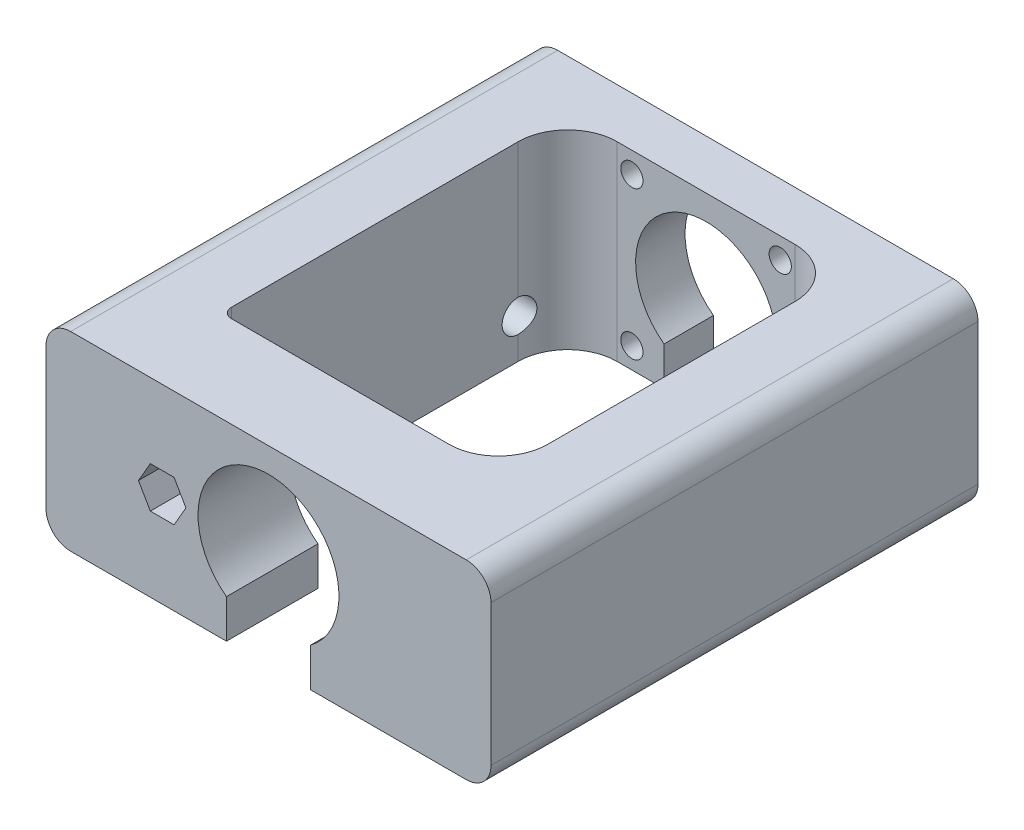
SolidWorks part; units mm, degrees
ref_plane "Front Plane" through (0, 0, 0) normal (0, 0, 1) x (1, 0, 0)
ref_plane "Top Plane" through (0, 0, 0) normal (0, 1, 0) x (1, 0, 0)
ref_plane "Right Plane" through (0, 0, 0) normal (1, 0, 0) x (0, 0, -1)
sketch "Sketch1" plane through (0, 0, 0) normal (0, 0, 1) x (1, 0, 0)
  line L0 (-15, 19.25) -> (-30, 19.25)
  line L2 (-45, 14.25) -> (-45, -14.25)
  line L4 (-15, 19.25) -> (15, 19.25)
  line L6 (15, -19.25) -> (8.5, -19.25)
  line L11 (-30, -19.25) -> (-15, -19.25)
  line L12 (-30, 19.25) -> (-40, 19.25)
  line L13 (-30, -19.25) -> (-40, -19.25)
  line L14 (-8.5, -19.25) -> (-15, -19.25)
  line L15 (0, 0) -> (0, 9.3162)
  line L16 (30, -19.25) -> (15, -19.25)
  line L17 (8.5, -16.75) -> (8.5, -11.4373)
  line L18 (-8.5, -16.75) -> (-8.5, -11.4373)
  line L19 (-8.5, -16.75) -> (-8.5, -19.25)
  line L20 (8.5, -16.75) -> (8.5, -19.25)
  line L21 (15, 19.25) -> (30, 19.25)
  line L22 (30, -19.25) -> (40, -19.25)
  line L23 (30, 19.25) -> (40, 19.25)
  line L24 (45, 14.25) -> (45, -14.25)
  arc A0 (8.5, -11.4373) -> (-8.5, -11.4373) centre (0, 0) ccw
  circle A1 centre (15, 15) radius 2.25
  circle A2 centre (-15, 15) radius 2.25
  circle A3 centre (-15, -15) radius 2.25
  circle A4 centre (15, -15) radius 2.25
  arc A19 (-40, -19.25) -> (-45, -14.25) centre (-40, -14.25) cw
  arc A20 (-40, 19.25) -> (-45, 14.25) centre (-40, 14.25) ccw
  arc A21 (40, 19.25) -> (45, 14.25) centre (40, 14.25) cw
  arc A22 (40, -19.25) -> (45, -14.25) centre (40, -14.25) ccw
  point P5 (19.25, 15)
  point P7 (-10.75, 15)
  point P13 (-10.75, -15)
  point P18 (-25.25, 0)
  point P19 (19.25, -15)
  point P20 (-15, 15)
  point P22 (15, 15)
  point P24 (15, -15)
  point P26 (-15, -15)
  point P38 (-39.75, 0)
  point P39 (-20.75, 0)
  point P51 (39.75, 0)
  dimension "D1" = 2
  dimension "D3" = 5
  dimension "D2" = 2
extrude "Boss-Extrude1" add sketch "Sketch1" along normal blind 10
sketch "Sketch2" plane through (0, 0, 10) normal (0, 0, 1) x (1, 0, 0)
  line L12 (-45, 14.25) -> (-45, -14.25)
  line L14 (-40, 19.25) -> (-28, 19.25)
  line L15 (-28, 0) -> (-28, 19.25)
  line L16 (-28, 0) -> (-28, -19.25)
  line L17 (-40, -19.25) -> (-28, -19.25)
  line L19 (40, -19.25) -> (28, -19.25)
  line L20 (28, 0) -> (28, -19.25)
  line L21 (28, 0) -> (28, 19.25)
  line L22 (40, 19.25) -> (28, 19.25)
  line L23 (45, 14.25) -> (45, -14.25)
  arc A0 (40, 19.25) -> (45, 14.25) centre (40, 14.25) cw
  arc A16 (-45, -14.25) -> (-40, -19.25) centre (-40, -14.25) ccw
  arc A17 (-40, 19.25) -> (-45, 14.25) centre (-40, 14.25) ccw
  arc A18 (45, -14.25) -> (40, -19.25) centre (40, -14.25) cw
extrude "Boss-Extrude3" add sketch "Sketch2" along normal blind 70 separate body
sketch "Sketch4" plane through (0, 0, 80) normal (0, 0, 1) x (1, 0, 0)
  line L5 (-28, -19.25) -> (-28, 19.25)
  line L7 (-45, 14.25) -> (-45, -14.25)
  line L11 (-45, 14.25) -> (-45, -14.25)
  line L21 (-40, 19.25) -> (40, 19.25)
  line L22 (-40, -19.25) -> (-8.5, -19.25)
  line L23 (-40, -19.25) -> (-28, -19.25)
  line L25 (-28, 19.25) -> (-40, 19.25)
  line L27 (-8.5, -11.4373) -> (-8.5, -19.25) construction
  line L28 (8.5, -19.25) -> (8.5, -11.4373) construction
  line L29 (40, 19.25) -> (28, 19.25)
  line L30 (28, 19.25) -> (28, -19.25)
  line L31 (28, -19.25) -> (40, -19.25)
  line L32 (45, -14.25) -> (45, 14.25)
  line L36 (45, -14.25) -> (45, 14.25)
  line L37 (-8.5, -11.4373) -> (-8.5, -19.25)
  line L38 (8.5, -19.25) -> (8.5, -11.4373)
  line L39 (8.5, -19.25) -> (40, -19.25)
  circle A1 centre (-21.5, 0) radius 3.5
  arc A2 (-45, -14.25) -> (-40, -19.25) centre (-40, -14.25) ccw
  arc A3 (-40, 19.25) -> (-45, 14.25) centre (-40, 14.25) ccw
  arc A4 (-45, -14.25) -> (-40, -19.25) centre (-40, -14.25) ccw
  arc A5 (-40, 19.25) -> (-45, 14.25) centre (-40, 14.25) ccw
  arc A11 (8.5, -11.4373) -> (-8.5, -11.4373) centre (0, 0) ccw construction
  arc A12 (45, 14.25) -> (40, 19.25) centre (40, 14.25) ccw
  arc A13 (40, -19.25) -> (45, -14.25) centre (40, -14.25) ccw
  arc A14 (45, 14.25) -> (40, 19.25) centre (40, 14.25) ccw
  arc A15 (40, -19.25) -> (45, -14.25) centre (40, -14.25) ccw
  arc A17 (8.5, -11.4373) -> (-8.5, -11.4373) centre (0, 0) ccw
  dimension "D3" = 0
  dimension "D1" = 0
extrude "Boss-Extrude4" add sketch "Sketch4" along normal blind 10
sketch "Sketch6" plane through (0, 0, 90) normal (0, 0, 1) x (1, 0, 0)
  line L6 (-40, -19.25) -> (-8.5, -19.25)
  line L8 (-40, -19.25) -> (-8.5, -19.25)
  line L9 (45, -14.25) -> (45, 14.25)
  line L10 (-45, 14.25) -> (-45, -14.25)
  line L11 (45, -14.25) -> (45, 14.25)
  line L16 (-45, 14.25) -> (-45, -14.25)
  line L21 (-16.7, 0) -> (-19.1, 4.1569)
  line L22 (-19.1, 4.1569) -> (-23.9, 4.1569)
  line L23 (-23.9, 4.1569) -> (-26.3, 0)
  line L24 (40, 19.25) -> (-40, 19.25)
  line L25 (40, 19.25) -> (-40, 19.25)
  line L26 (-26.3, 0) -> (-23.9, -4.1569)
  line L27 (-23.9, -4.1569) -> (-19.1, -4.1569)
  line L28 (-19.1, -4.1569) -> (-16.7, 0)
  line L30 (8.5, -11.4373) -> (8.5, -19.25)
  line L31 (8.5, -11.4373) -> (8.5, -19.25)
  line L32 (8.5, -19.25) -> (40, -19.25)
  line L33 (8.5, -19.25) -> (40, -19.25)
  line L34 (-8.5, -19.25) -> (-8.5, -11.4373)
  line L35 (-8.5, -19.25) -> (-8.5, -11.4373)
  circle A0 centre (-21.5, 0) radius 4.8 construction
  arc A5 (40, -19.25) -> (45, -14.25) centre (40, -14.25) ccw
  arc A6 (40, -19.25) -> (45, -14.25) centre (40, -14.25) ccw
  arc A9 (45, 14.25) -> (40, 19.25) centre (40, 14.25) ccw
  arc A10 (-40, 19.25) -> (-45, 14.25) centre (-40, 14.25) ccw
  arc A11 (-45, -14.25) -> (-40, -19.25) centre (-40, -14.25) ccw
  arc A16 (-40, 19.25) -> (-45, 14.25) centre (-40, 14.25) ccw
  arc A17 (-45, -14.25) -> (-40, -19.25) centre (-40, -14.25) ccw
  arc A18 (45, 14.25) -> (40, 19.25) centre (40, 14.25) ccw
  arc A20 (8.5, -11.4373) -> (-8.5, -11.4373) centre (0, 0) ccw
  arc A21 (8.5, -11.4373) -> (-8.5, -11.4373) centre (0, 0) ccw
  dimension "D1" = 0
extrude "Boss-Extrude5" add sketch "Sketch6" along normal blind 8.5
sketch "Sketch5" plane through (0, 0, 90) normal (0, 0, 1) x (1, 0, 0)
  circle A0 centre (-21.5, 0) radius 3.5
combine bodies "Combine1" operation type add bodies to combine 103 111 113
fillet "Fillet2" radius 2 1 edges at (-28, 0, 80)
fillet "Fillet3" radius 10 3 edges at (-28, 0, 10) (28, 0, 80) (28, 0, 10)
sketch "Sketch7" plane through (-28, 0, 0) normal (1, 0, 0) x (0, 0, -1)
  circle A0 centre (-20, -11.25) radius 3.25
extrude "Cut-Extrude1" cut sketch "Sketch7" against normal through all and the other way blind 10
